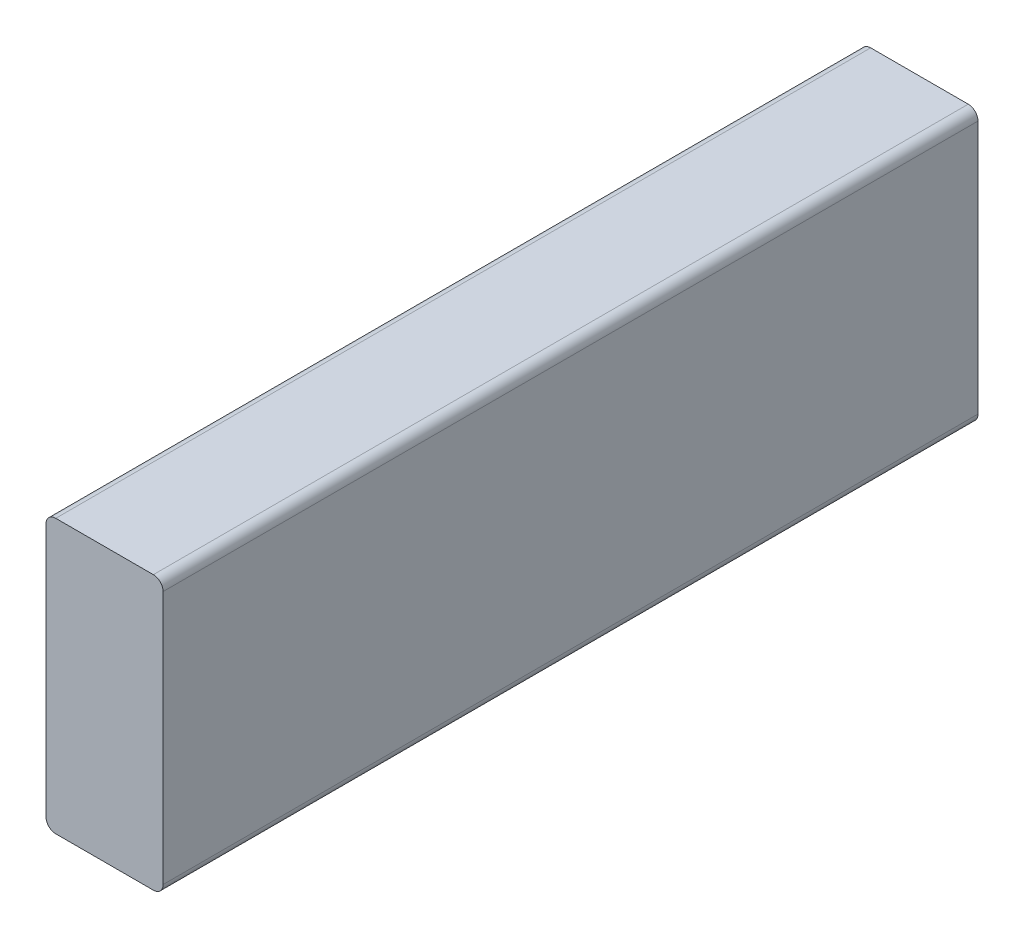
SolidWorks part; units mm, degrees
material "Pine"
ref_plane "Front Plane" through (0, 0, 0) normal (0, 0, 1) x (1, 0, 0)
ref_plane "Top Plane" through (0, 0, 0) normal (0, 1, 0) x (1, 0, 0)
ref_plane "Right Plane" through (0, 0, 0) normal (1, 0, 0) x (0, 0, -1)
sketch "Sketch1" plane through (0, 0, 0) normal (0, 0, 1) x (1, 0, 0)
  line L1 (0, 0) -> (38.1, 0)
  line L2 (0, 0) -> (0, 88.9)
  line L3 (0, 88.9) -> (38.1, 88.9)
  line L4 (38.1, 0) -> (38.1, 88.9)
  dimension "D1" = 38.1
  dimension "D2" = 88.9
extrude "Boss-Extrude1" add sketch "Sketch1" against normal blind 265.1125
fillet "Fillet1" radius 3.175 4 edges at (0, 0, -132.5562) (38.1, 0, -132.5562) (0, 88.9, -132.5562) (38.1, 88.9, -132.5562)
